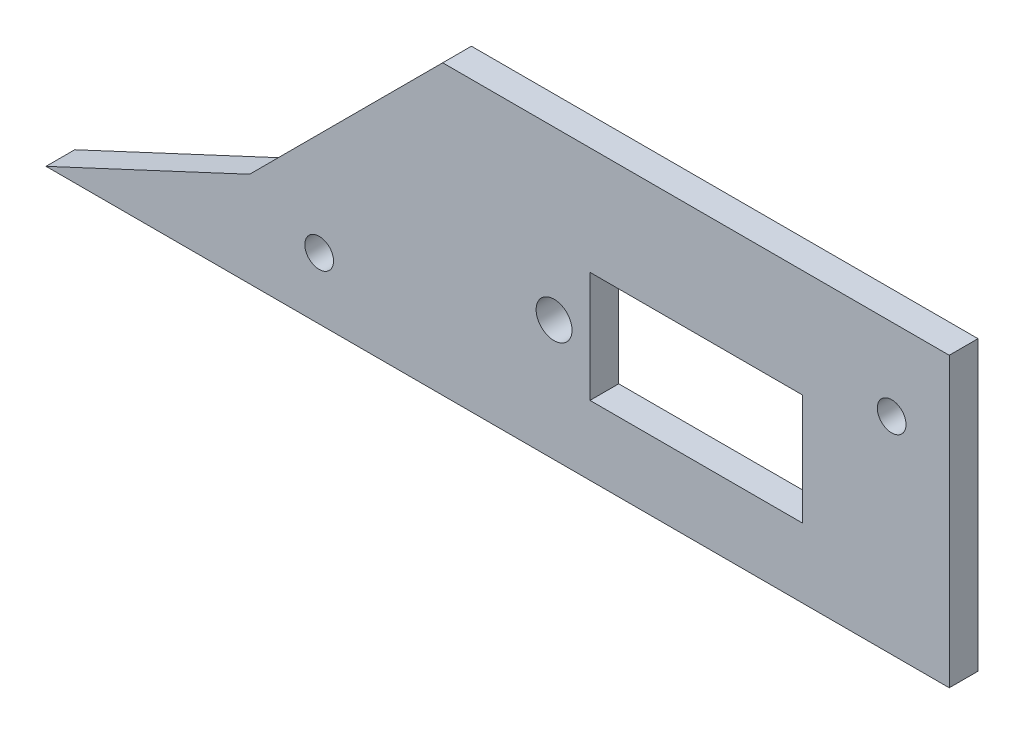
SolidWorks part; units mm, degrees
ref_plane "Спереди" through (0, 0, 0) normal (0, 0, 1) x (1, 0, 0)
ref_plane "Сверху" through (0, 0, 0) normal (0, 1, 0) x (1, 0, 0)
ref_plane "Справа" through (0, 0, 0) normal (1, 0, 0) x (0, 0, -1)
sketch "Эскиз1" plane through (0, 0, 0) normal (0, 0, 1) x (1, 0, 0)
  line L1 (-10, -36.46) -> (4.7983, -36.46)
  line L2 (-10, -36.46) -> (-10, -43.6789)
  line L4 (4.7983, -36.46) -> (4.7983, -43.6789)
  line L10 (15, -49) -> (15, -28.9578)
  line L11 (15, -28.9578) -> (-20.2514, -28.9578)
  line L12 (-20.2514, -28.9578) -> (-33.6865, -42.3929)
  line L13 (-33.6865, -42.3929) -> (-47.8555, -49)
  line L14 (-47.8555, -49) -> (15, -49)
  line L16 (-10, -43.6789) -> (-10, -44.1789)
  line L17 (-10, -44.1789) -> (4.7983, -44.1789)
  line L18 (4.7983, -43.6789) -> (4.7983, -44.1789)
  circle A0 centre (-12.5, -40.5789) radius 1.25
  circle A1 centre (-28.8455, -44.7101) radius 1
  circle A2 centre (10.9921, -34.6416) radius 1
extrude "Бобышка-Вытянуть1" add sketch "Эскиз1" along normal blind 2 contours L10 L11 L12 L13 L14
